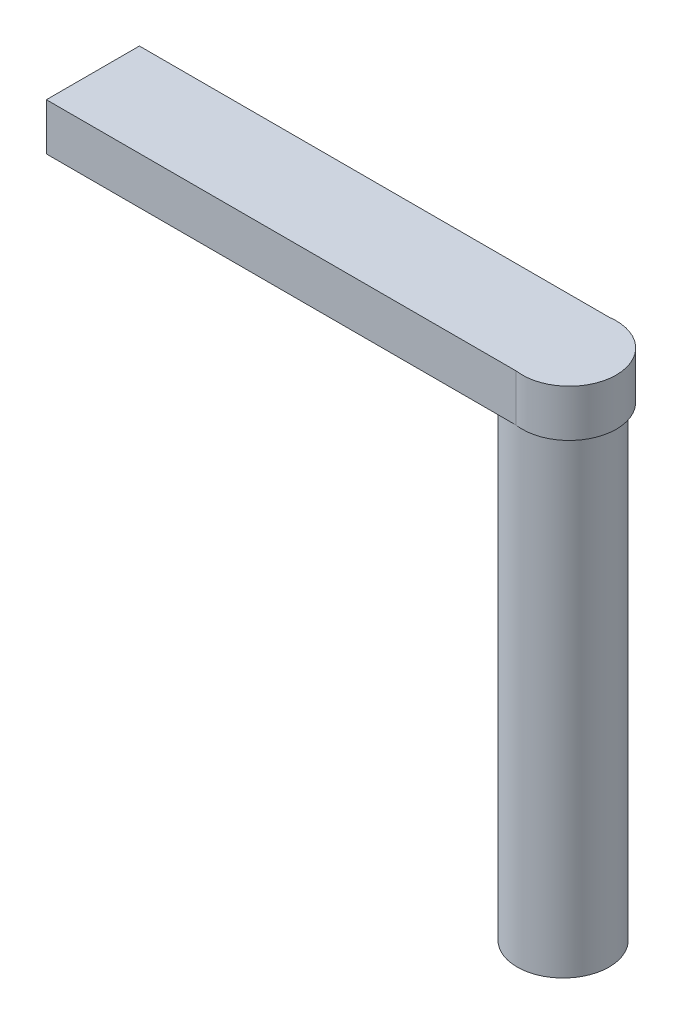
SolidWorks part; units mm, degrees
ref_plane "Front Plane" through (0, 0, 0) normal (0, 0, 1) x (1, 0, 0)
ref_plane "Top Plane" through (0, 0, 0) normal (0, 1, 0) x (1, 0, 0)
ref_plane "Right Plane" through (0, 0, 0) normal (1, 0, 0) x (0, 0, -1)
sketch "Sketch1" plane through (0, 0, 0) normal (0, 1, 0) x (1, 0, 0)
  circle A0 centre (0, 0) radius 4.9
  dimension "D1" = 9.8
extrude "Boss-Extrude1" add sketch "Sketch1" along normal blind 50
sketch "Sketch2" plane through (0, 50, 0) normal (0, 1, 0) x (1, 0, 0)
  line L1 (0, 4.9) -> (-50, 4.9)
  line L3 (0, -5) -> (-50, -5)
  line L4 (-50, 4.9) -> (-50, -5)
  circle A0 centre (0, 0) radius 4.9 construction
  arc A1 (0, -5) -> (0, 4.9) centre (0.7053, -0.05) ccw
  dimension "D1" = 50
extrude "Boss-Extrude2" add sketch "Sketch2" along normal blind 5
